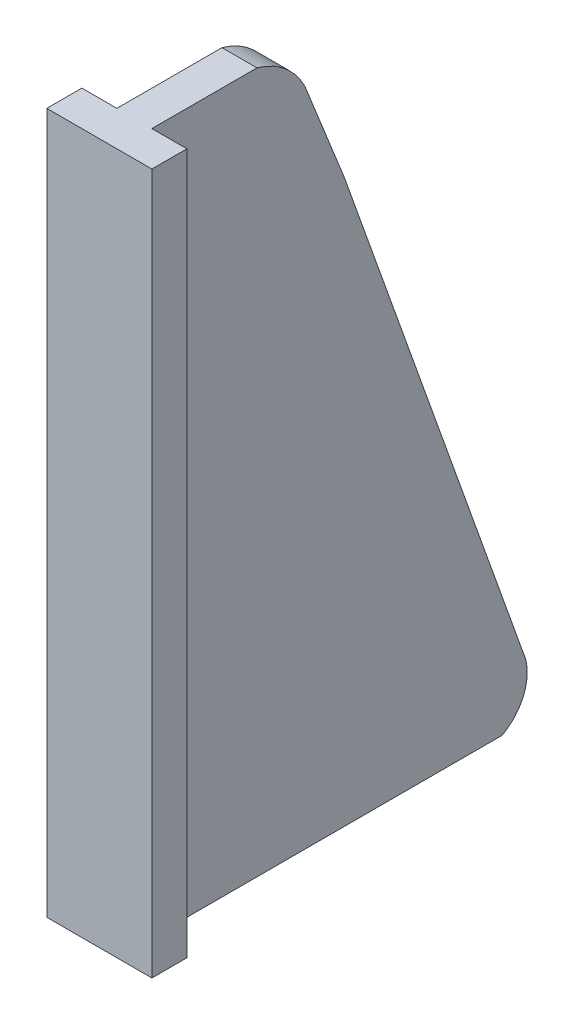
SolidWorks part; units mm, degrees
ref_plane "Plano frontal" through (0, 0, 0) normal (0, 0, 1) x (1, 0, 0)
ref_plane "Plano superior" through (0, 0, 0) normal (0, 1, 0) x (1, 0, 0)
ref_plane "Plano direito" through (0, 0, 0) normal (1, 0, 0) x (0, 0, -1)
sketch "Esboço1" plane through (0, 0, 0) normal (1, 0, 0) x (0, 0, -1)
  line L0 (0, 0) -> (0, 200)
  line L2 (0, 0) -> (110, 0)
  line L3 (115.9213, 17.653) -> (64.8176, 160.7694)
  line L4 (137.2453, 12) -> (-59.9329, 12) construction
  line L5 (103.4996, 64.5384) -> (103.4996, -33.7696) construction
  line L6 (0, 200) -> (40.0204, 200)
  line L7 (64.8176, 160.7694) -> (53.7187, 188.5)
  arc A2 (115.9213, 17.653) -> (110, 0) centre (103.4996, 12) cw
  arc A5 (40.0204, 200) -> (53.7187, 188.5) centre (34.1413, 179.0887) cw
  dimension "D1" = 200
  dimension "D2" = 110
  dimension "D5" = 12
extrude "Ressalto-extrusão1" add sketch "Esboço1" along normal blind 30
ref_plane "Plano2" through (20, 0, 0) normal (1, 0, 0) x (0, 0, -1)
sketch "Esboço7" plane through (20, 0, 0) normal (1, 0, 0) x (0, 0, -1)
  line L0 (0, 200) -> (0, 0) construction
  line L1 (10, -0.7651) -> (134.8312, -0.7651)
  line L2 (10, -0.7651) -> (10, 204.644)
  line L3 (10, 204.644) -> (134.8312, 204.644)
  line L4 (134.8312, -0.7651) -> (134.8312, 204.644)
  dimension "D1" = 10
extrude "Corte-extrusão1" cut sketch "Esboço7" along normal blind 26
ref_plane "Plano4" through (10, 0, 0) normal (-1, 0, 0) x (0, 0, 1)
sketch "Esboço9" plane through (10, 0, 0) normal (-1, 0, 0) x (0, 0, 1)
  line L0 (0, 200) -> (0, 0) construction
  line L1 (-118.1037, -3.3125) -> (-10, -3.3125)
  line L2 (-118.1037, -3.3125) -> (-118.1037, 203.1745)
  line L3 (-118.1037, 203.1745) -> (-10, 203.1745)
  line L4 (-10, -3.3125) -> (-10, 203.1745)
  dimension "D1" = 10
extrude "Corte-extrusão2" cut sketch "Esboço9" along normal blind 72
